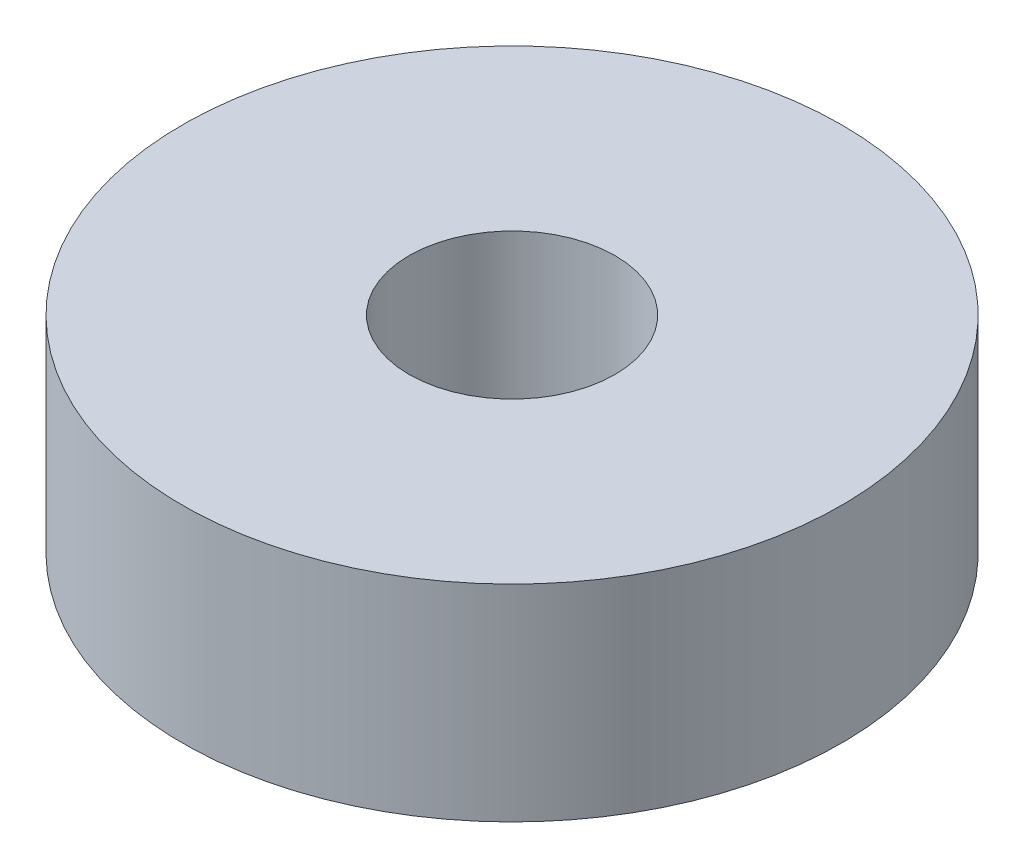
SolidWorks part; units mm, degrees
material "AISI 1020 Acier laminé à froid"
ref_plane "Plan de face" through (0, 0, 0) normal (0, 0, 1) x (1, 0, 0)
ref_plane "Plan de dessus" through (0, 0, 0) normal (0, 1, 0) x (1, 0, 0)
ref_plane "Plan de droite" through (0, 0, 0) normal (1, 0, 0) x (0, 0, -1)
sketch "Esquisse1" plane through (0, 0, 0) normal (0, 0, 1) x (1, 0, 0)
  line L0 (0, -2.3988) -> (0, 4.4273) construction
  line L2 (2.5, 2.5) -> (8, 2.5)
  line L3 (2.5, 2.5) -> (2.5, -2.5)
  line L4 (2.5, -2.5) -> (8, -2.5)
  line L5 (8, 2.5) -> (8, -2.5)
  point P7 (2.5, 0)
  dimension "D1" = 5
  dimension "D2" = 16
  dimension "D3" = 5
revolve "Révolution1" add sketch "Esquisse1" angle 360 about L0
